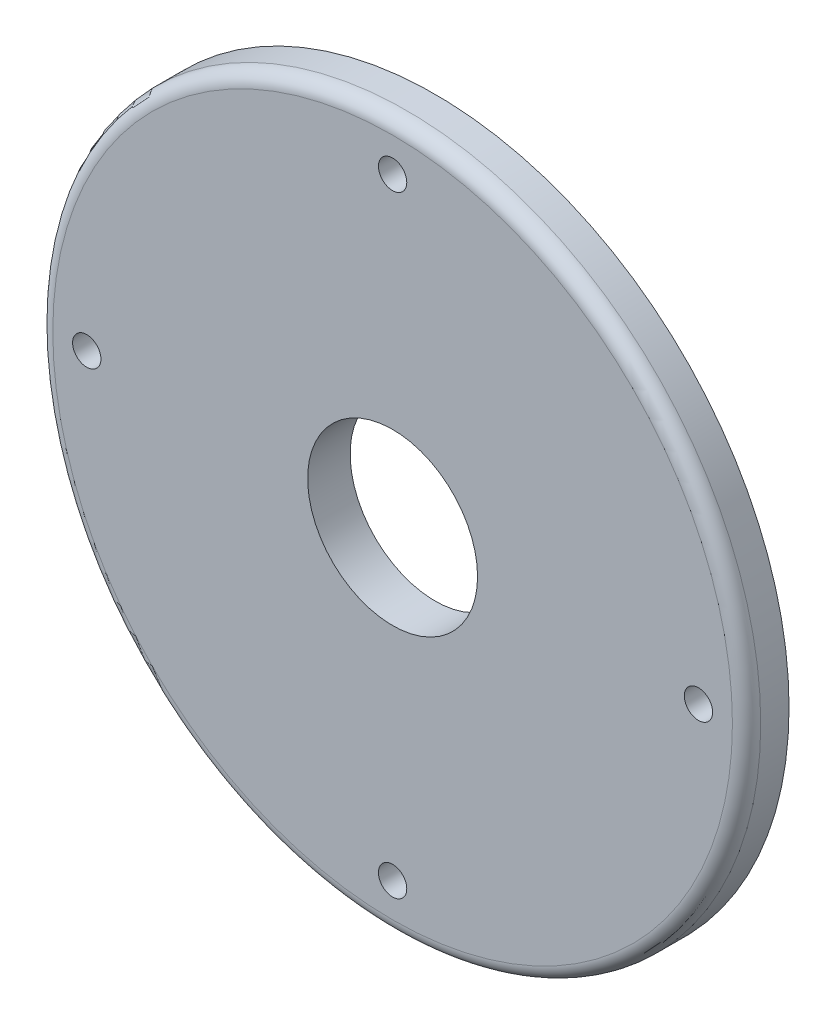
SolidWorks part; units mm, degrees
ref_plane "Front Plane" through (0, 0, 0) normal (0, 0, 1) x (1, 0, 0)
ref_plane "Top Plane" through (0, 0, 0) normal (0, 1, 0) x (1, 0, 0)
ref_plane "Right Plane" through (0, 0, 0) normal (1, 0, 0) x (0, 0, -1)
sketch "Sketch1" plane through (0, 0, 1301.6778) normal (0, 0, 1) x (1, 0, 0)
  circle A0 centre (678.3839, 875.198) radius 6
  circle A1 centre (678.3839, 896.7991) radius 1
  circle A2 centre (678.3839, 853.597) radius 1
  circle A3 centre (699.9849, 875.198) radius 1
  circle A4 centre (656.7828, 875.198) radius 1
  circle A5 centre (678.3839, 875.198) radius 25
extrude "Boss-Extrude1" add sketch "Sketch1" along normal blind 3
fillet "Fillet1" radius 1 1 edges at (703.3839, 875.198, 1304.6778)
